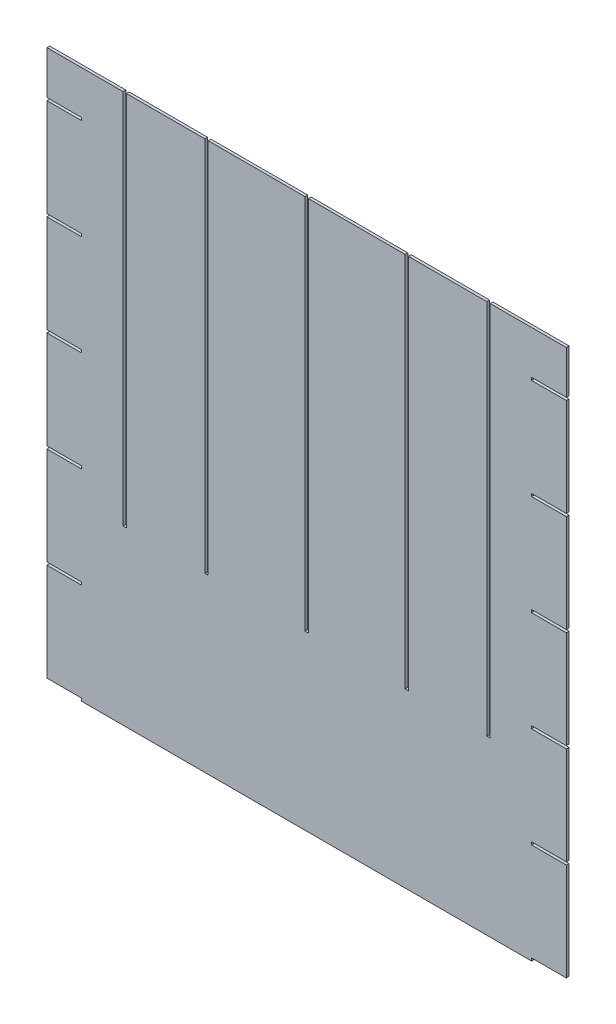
SolidWorks part; units mm, degrees
ref_plane "Front Plane" through (0, 0, 0) normal (0, 0, 1) x (1, 0, 0)
ref_plane "Top Plane" through (0, 0, 0) normal (0, 1, 0) x (1, 0, 0)
ref_plane "Right Plane" through (0, 0, 0) normal (1, 0, 0) x (0, 0, -1)
sketch "Model" plane through (0, 0, 0) normal (0, 0, 1) x (1, 0, 0)
  line L0 (-284.0992, 3) -> (-245.9797, 3)
  line L1 (-245.9797, 3) -> (-245.9797, 0)
  line L2 (245.9797, 0) -> (-245.9797, 0)
  line L3 (245.9797, 0) -> (245.9797, 3)
  line L4 (284.0992, 3) -> (245.9797, 3)
  line L5 (284.0992, 3) -> (284.0992, 110)
  line L6 (284.0992, 110) -> (245.9797, 110)
  line L7 (245.9797, 113) -> (245.9797, 110)
  line L8 (284.0992, 113) -> (245.9797, 113)
  line L9 (284.0992, 113) -> (284.0992, 220)
  line L10 (284.0992, 220) -> (245.9797, 220)
  line L11 (245.9797, 223) -> (245.9797, 220)
  line L12 (284.0992, 223) -> (245.9797, 223)
  line L13 (284.0992, 223) -> (284.0992, 330)
  line L14 (284.0992, 330) -> (245.9797, 330)
  line L15 (245.9797, 333) -> (245.9797, 330)
  line L16 (284.0992, 333) -> (245.9797, 333)
  line L17 (284.0992, 333) -> (284.0992, 440)
  line L18 (284.0992, 440) -> (245.9797, 440)
  line L19 (245.9797, 443) -> (245.9797, 440)
  line L20 (284.0992, 443) -> (245.9797, 443)
  line L21 (284.0992, 443) -> (284.0992, 550)
  line L22 (284.0992, 550) -> (245.9797, 550)
  line L23 (245.9797, 550) -> (245.9797, 553)
  line L24 (284.0992, 553) -> (245.9797, 553)
  line L25 (284.0992, 553) -> (284.0992, 600.2482)
  line L26 (200.7227, 600.2482) -> (284.0992, 600.2482)
  line L27 (200.7227, 600.2482) -> (200.7227, 188.6103)
  line L28 (200.7227, 188.6103) -> (197.1227, 188.6103)
  line L29 (197.1227, 188.6103) -> (197.1227, 600.2482)
  line L30 (111.3, 600.2482) -> (197.1227, 600.2482)
  line L31 (111.3, 600.2482) -> (111.3, 188.6103)
  line L32 (111.3, 188.6103) -> (107.7, 188.6103)
  line L33 (107.7, 188.6103) -> (107.7, 600.2482)
  line L34 (1.8, 600.2482) -> (107.7, 600.2482)
  line L35 (1.8, 600.2482) -> (1.8, 188.6103)
  line L36 (1.8, 188.6103) -> (-1.8, 188.6103)
  line L37 (-1.8, 188.6103) -> (-1.8, 600.2482)
  line L38 (-107.7, 600.2482) -> (-1.8, 600.2482)
  line L39 (-107.7, 600.2482) -> (-107.7, 188.6103)
  line L40 (-107.7, 188.6103) -> (-111.3, 188.6103)
  line L41 (-111.3, 188.6103) -> (-111.3, 600.2482)
  line L42 (-197.1227, 600.2482) -> (-111.3, 600.2482)
  line L43 (-197.1227, 600.2482) -> (-197.1227, 188.6103)
  line L44 (-197.1227, 188.6103) -> (-200.7227, 188.6103)
  line L45 (-200.7227, 188.6103) -> (-200.7227, 600.2482)
  line L46 (-284.0992, 600.2482) -> (-200.7227, 600.2482)
  line L47 (-284.0992, 553) -> (-284.0992, 600.2482)
  line L48 (-284.0992, 553) -> (-245.9797, 553)
  line L49 (-245.9797, 550) -> (-245.9797, 553)
  line L50 (-284.0992, 550) -> (-245.9797, 550)
  line L51 (-284.0992, 443) -> (-284.0992, 550)
  line L52 (-284.0992, 443) -> (-245.9797, 443)
  line L53 (-245.9797, 440) -> (-245.9797, 443)
  line L54 (-284.0992, 440) -> (-245.9797, 440)
  line L55 (-284.0992, 333) -> (-284.0992, 440)
  line L56 (-284.0992, 333) -> (-245.9797, 333)
  line L57 (-245.9797, 333) -> (-245.9797, 330)
  line L58 (-284.0992, 330) -> (-245.9797, 330)
  line L59 (-284.0992, 223) -> (-284.0992, 330)
  line L60 (-284.0992, 223) -> (-245.9797, 223)
  line L61 (-245.9797, 223) -> (-245.9797, 220)
  line L62 (-284.0992, 220) -> (-245.9797, 220)
  line L63 (-284.0992, 113) -> (-284.0992, 220)
  line L64 (-284.0992, 113) -> (-245.9797, 113)
  line L65 (-245.9797, 113) -> (-245.9797, 110)
  line L66 (-284.0992, 110) -> (-245.9797, 110)
  line L67 (-284.0992, 3) -> (-284.0992, 110)
extrude "Boss-Extrude1" add sketch "Model" along normal blind 3
